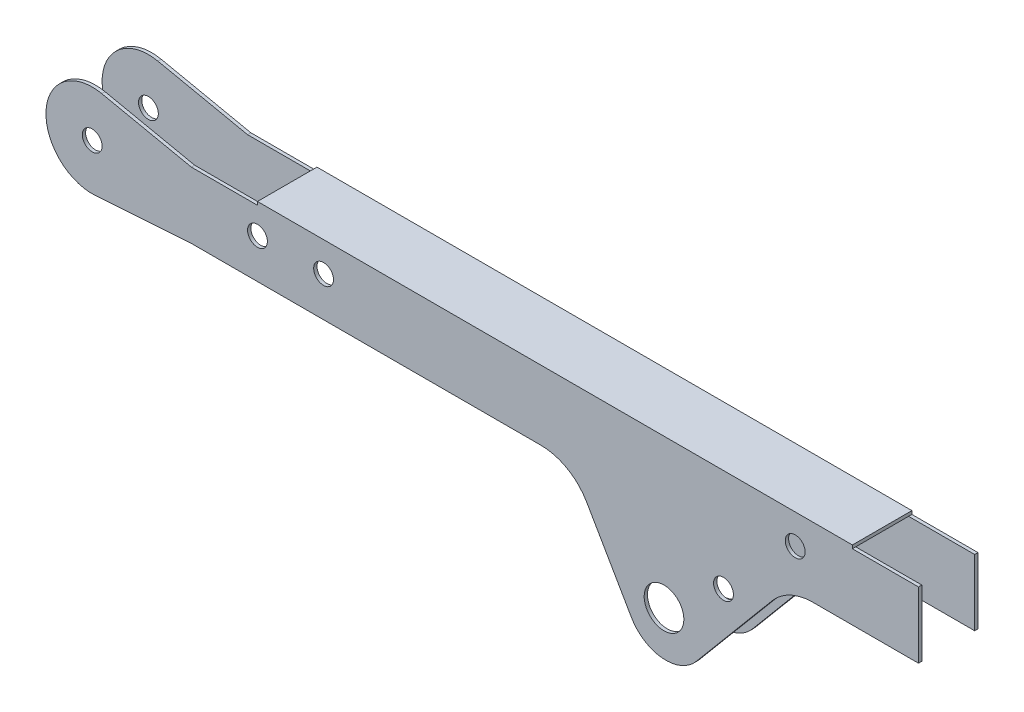
SolidWorks part; units mm, degrees
material "7075-T6，板材(SS)"
ref_plane "前视基准面" through (0, 0, 0) normal (0, 0, 1) x (1, 0, 0)
ref_plane "上视基准面" through (0, 0, 0) normal (0, 1, 0) x (1, 0, 0)
ref_plane "右视基准面" through (0, 0, 0) normal (1, 0, 0) x (0, 0, -1)
sketch "草图1" plane through (0, 0, 0) normal (0, 0, 1) x (1, 0, 0)
  line L0 (-28.9376, 11.8639) -> (81.0624, 11.8639)
  line L1 (-28.9376, 1.8639) -> (28.5624, 1.8639)
  line L2 (-49.4416, 7.8639) -> (82.0027, 7.8639) construction
  line L3 (-28.9376, 11.8639) -> (-42.4977, 14.7142)
  line L4 (-28.9376, 1.8639) -> (-43.4645, 0.8799)
  line L5 (28.5624, 1.8639) -> (41.9222, -21.276)
  line L6 (41.9222, -21.276) -> (61.3388, 1.8639)
  line L7 (81.0624, 11.8639) -> (81.0624, 1.8639)
  line L8 (61.3388, 1.8639) -> (81.0624, 1.8639)
  arc A0 (-42.4977, 14.7142) -> (-43.4645, 0.8799) centre (-43.9376, 7.8639) ccw
  circle A1 centre (-43.9376, 7.8639) radius 1.5
  circle A2 centre (42.5624, -10.1361) radius 3
  circle A3 centre (51.5624, -3.1361) radius 1.5
  circle A4 centre (-18.9376, 7.8639) radius 1.5
  circle A5 centre (-8.9376, 7.8639) radius 1.5
  circle A6 centre (62.4094, 7.8639) radius 1.5
  dimension "D1" = 3
  dimension "D2" = 14
  dimension "D12" = 6
  dimension "D14" = 3
  dimension "D20" = 3
  dimension "D21" = 3
  dimension "D22" = 3
  dimension "D3" = 110
  dimension "D4" = 14
  dimension "D5" = 10
  dimension "D6" = 15
  dimension "D7" = 15
  dimension "D8" = 4
  dimension "D9" = 86.5
  dimension "D10" = 60
  dimension "D11" = 50
  dimension "D15" = 5
  dimension "D16" = 23
  dimension "D17" = 12
  dimension "D18" = 25
  dimension "D19" = 35
extrude "凸台-拉伸1" add sketch "草图1" along normal blind 0.5
ref_plane "基准面1" through (0, 0, -8) normal (0, 0, 1) x (1, 0, 0)
sketch "草图3" plane through (0, 0, -8) normal (0, 0, 1) x (1, 0, 0)
  line L8 (41.9222, -21.276) -> (61.3388, 1.8639)
  line L9 (61.3388, 1.8639) -> (81.0624, 1.8639)
  line L10 (81.0624, 1.8639) -> (81.0624, 11.8639)
  line L11 (81.0624, 11.8639) -> (-28.9376, 11.8639)
  line L12 (-28.9376, 11.8639) -> (-42.4977, 14.7142)
  line L13 (-43.4645, 0.8799) -> (-28.9376, 1.8639)
  line L14 (-28.9376, 1.8639) -> (28.5624, 1.8639)
  line L15 (28.5624, 1.8639) -> (41.9222, -21.276)
  line L16 (41.9222, -21.276) -> (61.3388, 1.8639)
  line L17 (61.3388, 1.8639) -> (81.0624, 1.8639)
  line L18 (81.0624, 1.8639) -> (81.0624, 11.8639)
  line L19 (81.0624, 11.8639) -> (-28.9376, 11.8639)
  line L20 (-28.9376, 11.8639) -> (-42.4977, 14.7142)
  line L21 (-43.4645, 0.8799) -> (-28.9376, 1.8639)
  line L22 (-28.9376, 1.8639) -> (28.5624, 1.8639)
  line L23 (28.5624, 1.8639) -> (41.9222, -21.276)
  circle A1 centre (51.5624, -3.1361) radius 1.5
  circle A2 centre (51.5624, -3.1361) radius 1.5
  circle A3 centre (42.5624, -10.1361) radius 3
  circle A4 centre (42.5624, -10.1361) radius 3
  circle A5 centre (-43.9376, 7.8639) radius 1.5
  circle A6 centre (-43.9376, 7.8639) radius 1.5
  circle A7 centre (62.4094, 7.8639) radius 1.5
  circle A8 centre (62.4094, 7.8639) radius 1.5
  circle A9 centre (-8.9376, 7.8639) radius 1.5
  circle A10 centre (-8.9376, 7.8639) radius 1.5
  circle A11 centre (-18.9376, 7.8639) radius 1.5
  circle A12 centre (-18.9376, 7.8639) radius 1.5
  arc A13 (-42.4977, 14.7142) -> (-43.4645, 0.8799) centre (-43.9376, 7.8639) ccw
  arc A14 (-42.4977, 14.7142) -> (-43.4645, 0.8799) centre (-43.9376, 7.8639) ccw
  dimension "D1" = 0
  dimension "D2" = 0
  dimension "D3" = 0
  dimension "D4" = 0
  dimension "D5" = 0
  dimension "D6" = 0
  dimension "D7" = 0
extrude "凸台-拉伸2" add sketch "草图3" against normal blind 0.5 separate body
ref_plane "基准面3" through (0, 11.8639, 0) normal (0, 1, 0) x (1, 0, 0)
sketch "草图4" plane through (0, 11.8639, 0) normal (0, 1, 0) x (1, 0, 0)
  line L0 (71.0624, 8.5) -> (71.0624, -0.5)
  line L1 (71.0624, -0.5) -> (-18.9376, -0.5)
  line L2 (81.0624, -0.5) -> (-28.9376, -0.5) construction
  line L3 (-18.9376, -0.5) -> (-18.9376, 8.5)
  line L4 (81.0624, 8.5) -> (-28.9376, 8.5) construction
  line L5 (-18.9376, 8.5) -> (71.0624, 8.5)
  line L6 (-43.9376, 8.5) -> (-43.9376, 8) construction
  line L8 (81.0624, 13.7104) -> (81.0624, -2.5495) construction
  dimension "D1" = 25
  dimension "D2" = 10
extrude "凸台-拉伸3" add sketch "草图4" along normal blind 0.5
fillet "圆角1" radius 8 4 edges at (28.5624, 1.8639, 0.25) (28.5624, 1.8639, -8.25) (61.3388, 1.8639, 0.25) (61.3388, 1.8639, -8.25)
fillet "圆角2" radius 6 2 edges at (41.9222, -21.276, -8.25) (41.9222, -21.276, 0.25)
